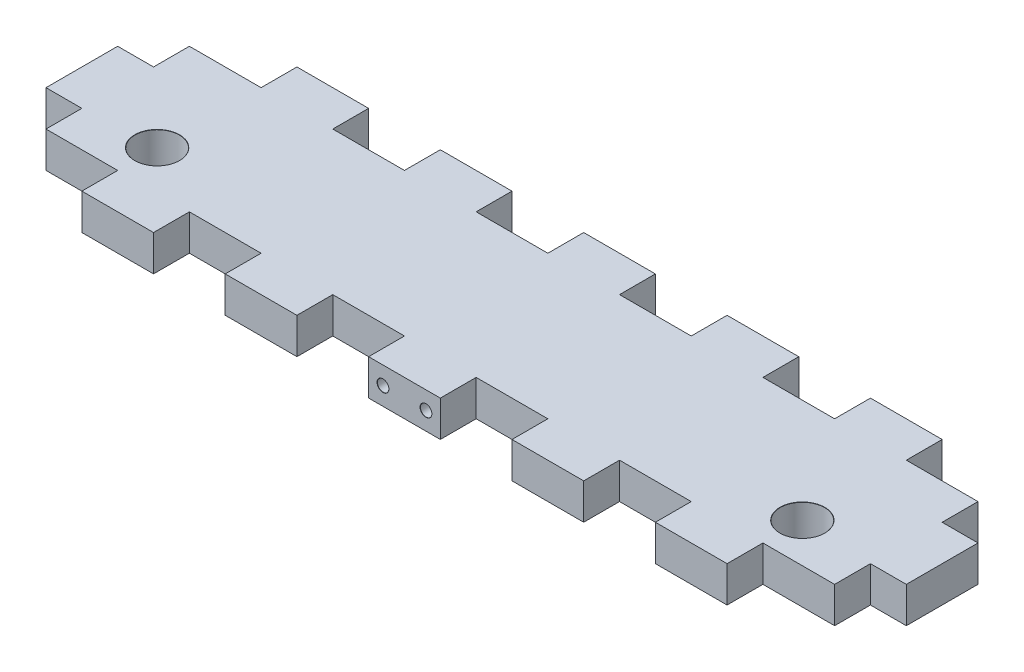
SolidWorks part; units mm, degrees
ref_plane "Front Plane" through (0, 0, 0) normal (0, 0, 1) x (1, 0, 0)
ref_plane "Top Plane" through (0, 0, 0) normal (0, 1, 0) x (1, 0, 0)
ref_plane "Right Plane" through (0, 0, 0) normal (1, 0, 0) x (0, 0, -1)
sketch "Sketch1" plane through (0, 0, 0) normal (0, 1, 0) x (1, 0, 0)
  line L0 (45, 15) -> (35, 15)
  line L1 (35, 15) -> (35, 10)
  line L2 (35, 10) -> (25, 10)
  line L3 (25, 10) -> (25, 15)
  line L4 (25, 15) -> (15, 15)
  line L5 (15, 15) -> (15, 10)
  line L6 (15, 10) -> (5, 10)
  line L7 (5, 10) -> (5, 15)
  line L8 (5, 15) -> (-5, 15)
  line L9 (-5, 15) -> (-5, 10)
  line L10 (-5, 10) -> (-15, 10)
  line L11 (-15, 10) -> (-15, 15)
  line L12 (-15, 15) -> (-25, 15)
  line L13 (-25, 15) -> (-25, 10)
  line L14 (-25, 10) -> (-35, 10)
  line L15 (-35, 10) -> (-35, 15)
  line L16 (-35, 15) -> (-45, 15)
  line L17 (-45, 15) -> (-45, 10)
  line L18 (-45, 10) -> (-55, 10)
  line L19 (-55, 10) -> (-55, 5)
  line L20 (-55, 5) -> (-60, 5)
  line L21 (-60, 5) -> (-60, -5)
  line L22 (-60, -5) -> (-55, -5)
  line L23 (-55, -5) -> (-55, -10)
  line L24 (-55, -10) -> (-45, -10)
  line L25 (-45, -10) -> (-45, -15)
  line L26 (-45, -15) -> (-35, -15)
  line L27 (-35, -15) -> (-35, -10)
  line L28 (-35, -10) -> (-25, -10)
  line L29 (-25, -10) -> (-25, -15)
  line L30 (-25, -15) -> (-15, -15)
  line L31 (-15, -15) -> (-15, -10)
  line L32 (-15, -10) -> (-5, -10)
  line L33 (-5, -10) -> (-5, -15)
  line L34 (-5, -15) -> (5, -15)
  line L35 (5, -15) -> (5, -10)
  line L36 (5, -10) -> (15, -10)
  line L37 (15, -10) -> (15, -15)
  line L38 (15, -15) -> (25, -15)
  line L39 (25, -15) -> (25, -10)
  line L40 (25, -10) -> (35, -10)
  line L41 (35, -10) -> (35, -15)
  line L42 (35, -15) -> (45, -15)
  line L43 (45, -15) -> (45, -10)
  line L44 (45, -10) -> (55, -10)
  line L45 (55, -10) -> (55, -5)
  line L46 (55, -5) -> (60, -5)
  line L47 (60, -5) -> (60, 5)
  line L48 (60, 5) -> (55, 5)
  line L49 (55, 5) -> (55, 10)
  line L50 (55, 10) -> (45, 10)
  line L51 (45, 10) -> (45, 15)
  line L52 (-60, 15) -> (60, -15) construction
  line L53 (-60, 5) -> (-60, 15) construction
  line L54 (-60, 15) -> (-45, 15) construction
  line L55 (45, -15) -> (60, -15) construction
  line L56 (60, -15) -> (60, -5) construction
  point P54 (0, 0)
  dimension "D1" = 0
extrude "Boss-Extrude1" add sketch "Sketch1" along normal mid plane 5
sketch "Sketch2" plane through (0, 2.5, 0) normal (0, 1, 0) x (1, 0, 0)
  text T0 "Front/Back"
extrude "Cut-Extrude1" [suppressed] cut sketch "Sketch2" against normal blind 3
sketch "Sketch3" plane through (0, 0, 15) normal (0, 0, 1) x (1, 0, 0)
  line L0 (-3, 0) -> (3, 0) construction
  line L1 (-5, -2.5) -> (5, -2.5) construction
  point P0 (-3, 0)
  point P1 (3, 0)
  point P2 (0, 0)
  dimension "D1" = 6
  dimension "D2" = 2.5
hole_wizard "Tap Drill for M2 Tap1" positions "Sketch3" profile "Sketch4" hole size "M2" standard "IS"
sketch "Sketch4" plane through (-3, 0, 15) normal (1, 0, 0) x (0, -1, 0)
  line L0 (0, 0) -> (0, 12.4807)
  line L1 (0, 12.4807) -> (0.8, 12)
  line L2 (0.8, 12) -> (0.8, 0.025)
  line L3 (0.8, 0.025) -> (0.825, 0)
  line L5 (0.825, 0) -> (0, 0)
  line L6 (-0.8, 0.025) -> (-0.825, 0) construction
  line L10 (0, 12.4807) -> (-0.8, 12) construction
  line L11 (0, -6.35) -> (0, 107.95) construction
  dimension "Hole Dia." = 1.6
  dimension "Hole Depth" = 12
  dimension "Near C'Sink Dia." = 1.65
  dimension "Near C'Sink Angle" = 90
  dimension "Drill Angle" = 118
sketch "Sketch5" plane through (0, 2.5, 0) normal (0, 1, 0) x (1, 0, 0)
  line L0 (-45, -4.5) -> (45, -4.5) construction
  line L1 (-35, 15) -> (-45, 15) construction
  line L2 (-60, 5) -> (-60, -5) construction
  line L3 (60, -5) -> (60, 5) construction
  point P0 (-45, -4.5)
  point P1 (45, -4.5)
  dimension "D1" = 19.5
  dimension "D2" = 15
  dimension "D3" = 15
hole_wizard "Ø6.2 (6.2) Diameter Hole1" positions "Sketch5" profile "Sketch6" hole size "Ø6.2" standard "ISO" end condition through all
sketch "Sketch6" plane through (-45, 2.5, 4.5) normal (1, 0, 0) x (0, 0, 1)
  line L0 (0, 0) -> (0, 5)
  line L1 (0, 5) -> (3.1, 5)
  line L2 (3.1, 5) -> (3.1, 0.025)
  line L3 (3.1, 0.025) -> (3.125, 0)
  line L5 (3.125, 0) -> (0, 0)
  line L6 (-3.1, 0.025) -> (-3.125, 0) construction
  line L11 (0, -6.35) -> (0, 107.95) construction
  dimension "Thru Hole Dia." = 6.2
  dimension "Thru Hole Depth" = 5
  dimension "Near C'Sink Dia." = 6.25
  dimension "Near C'Sink Angle" = 90
